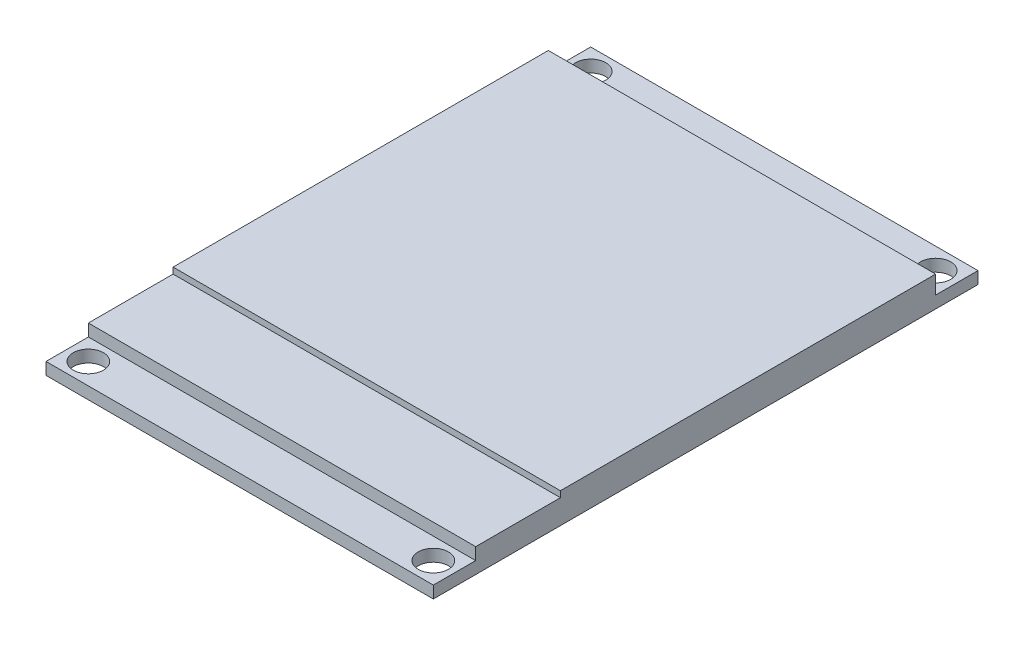
SolidWorks part; units mm, degrees
ref_plane "前视基准面" through (0, 0, 0) normal (0, 0, 1) x (1, 0, 0)
ref_plane "上视基准面" through (0, 0, 0) normal (0, 1, 0) x (1, 0, 0)
ref_plane "右视基准面" through (0, 0, 0) normal (1, 0, 0) x (0, 0, -1)
sketch "草图1" plane through (0, 0, 0) normal (0, 1, 0) x (1, 0, 0)
  line L0 (16, 0) -> (16, 51.1718) construction
  line L1 (0, 0) -> (32, 0)
  line L2 (0, 0) -> (0, 45)
  line L3 (0, 45) -> (32, 45)
  line L4 (32, 0) -> (32, 45)
  line L5 (0, 22.5) -> (38.1062, 22.5) construction
  circle A0 centre (30.25, 43.25) radius 1.25
  circle A1 centre (30.25, 1.75) radius 1.25
  circle A2 centre (1.75, 1.75) radius 1.25
  circle A3 centre (1.75, 43.25) radius 1.25
  dimension "D3" = 41.5
  dimension "D5" = 2.5
  dimension "D1" = 32
  dimension "D2" = 45
  dimension "D4" = 28.5
extrude "凸台-拉伸1" add sketch "草图1" along normal blind 1
sketch "草图2" plane through (0, 1, 0) normal (0, 1, 0) x (1, 0, 0)
  line L0 (0, 45) -> (0, 0) construction
  line L1 (0, 41.5) -> (32, 41.5)
  line L2 (0, 41.5) -> (0, 10.5)
  line L3 (0, 10.5) -> (32, 10.5)
  line L4 (32, 41.5) -> (32, 10.5)
  line L5 (32, 0) -> (32, 45) construction
  line L6 (32, 45) -> (0, 45) construction
  dimension "D1" = 3.5
  dimension "D2" = 31
extrude "凸台-拉伸2" add sketch "草图2" along normal blind 1.5
sketch "草图3" plane through (0, 1, 0) normal (0, 1, 0) x (1, 0, 0)
  line L1 (0, 10.5) -> (32, 10.5)
  line L2 (0, 10.5) -> (0, 3.5)
  line L3 (0, 3.5) -> (32, 3.5)
  line L4 (32, 10.5) -> (32, 3.5)
  line L5 (32, 0) -> (32, 10.5) construction
  line L6 (32, 41.5) -> (0, 41.5) construction
  point P7 (0, 0)
  dimension "D1" = 38
extrude "凸台-拉伸3" add sketch "草图3" along normal blind 1
